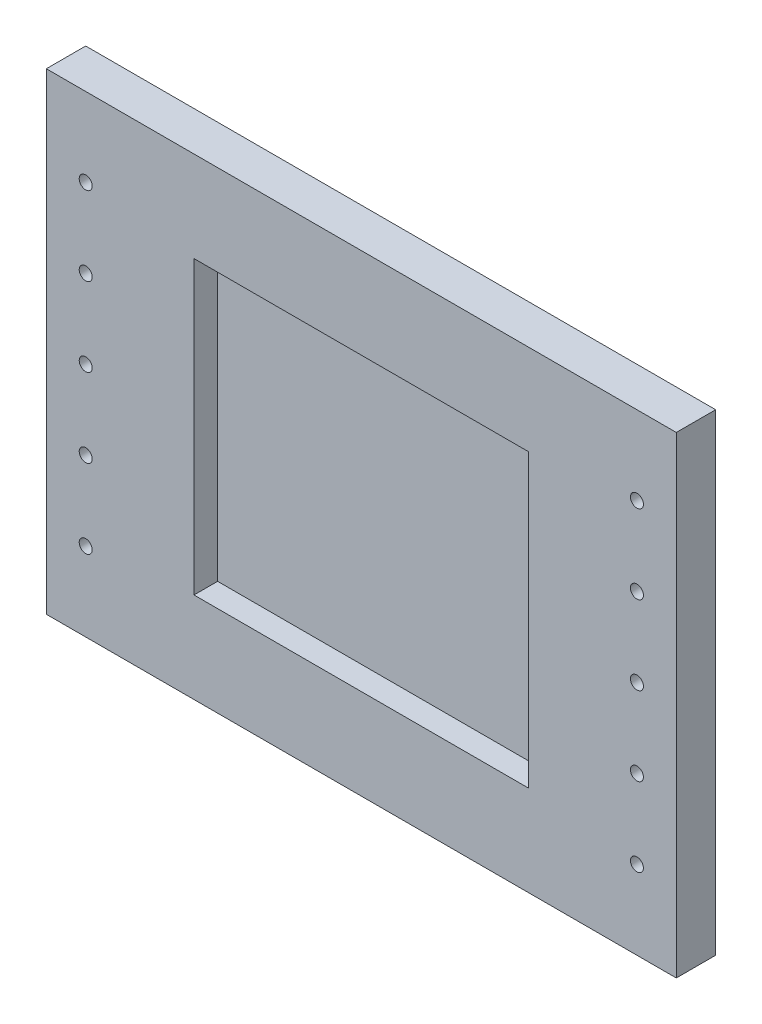
SolidWorks part; units mm, degrees
ref_plane "前视基准面" through (0, 0, 0) normal (0, 0, 1) x (1, 0, 0)
ref_plane "上视基准面" through (0, 0, 0) normal (0, 1, 0) x (1, 0, 0)
ref_plane "右视基准面" through (0, 0, 0) normal (1, 0, 0) x (0, 0, -1)
other "Configuration Table"
sketch "草图1" plane through (0, 0, 0) normal (0, 0, 1) x (1, 0, 0)
  line L1 (-80, 60) -> (80, 60)
  line L2 (-80, 60) -> (-80, -60)
  line L3 (-80, -60) -> (80, -60)
  line L4 (80, 60) -> (80, -60)
  line L5 (-80, 60) -> (80, -60) construction
  line L6 (-80, -60) -> (80, 60) construction
  point P0 (0, 0)
  dimension "D1" = 160
  dimension "D2" = 120
extrude "凸台-拉伸1" add sketch "草图1" along normal blind 10
sketch "草图2" plane through (0, 0, 10) normal (0, 0, 1) x (1, 0, 0)
  line L0 (-80, 0) -> (80, 0) construction
  line L1 (-80, 60) -> (-80, -60) construction
  line L2 (80, -60) -> (80, 60) construction
  line L3 (0, 60) -> (0, -60) construction
  line L4 (80, 60) -> (-80, 60) construction
  line L5 (-80, -60) -> (80, -60) construction
  line L7 (-42.5, 37) -> (42.5, 37)
  line L8 (-42.5, 37) -> (-42.5, -37)
  line L9 (-42.5, -37) -> (42.5, -37)
  line L10 (42.5, 37) -> (42.5, -37)
  line L11 (-42.5, 37) -> (42.5, -37) construction
  line L12 (-42.5, -37) -> (42.5, 37) construction
  point P12 (0, 0)
  dimension "D1" = 85
  dimension "D2" = 74
extrude "切除-拉伸1" cut sketch "草图2" against normal blind 6
sketch "草图3" plane through (0, 0, 0) normal (0, 0, -1) x (-1, 0, 0)
  line L0 (-80, -60) -> (-80, 60) construction
  line L1 (-80, 60) -> (80, 60) construction
  circle A0 centre (-70, 40) radius 1.65
  circle A1 centre (-70, 20) radius 1.65
  circle A2 centre (-70, 0) radius 1.65
  circle A3 centre (-70, -20) radius 1.65
  circle A4 centre (-70, -40) radius 1.65
  dimension "D1" = 3.3
  dimension "D2" = 10
  dimension "D3" = 20
  dimension "D4" = 5
extrude "切除-拉伸2" cut sketch "草图3" against normal through all
mirror "镜向1" about plane through (0, 0, 0) normal (1, 0, 0) of "切除-拉伸2"
